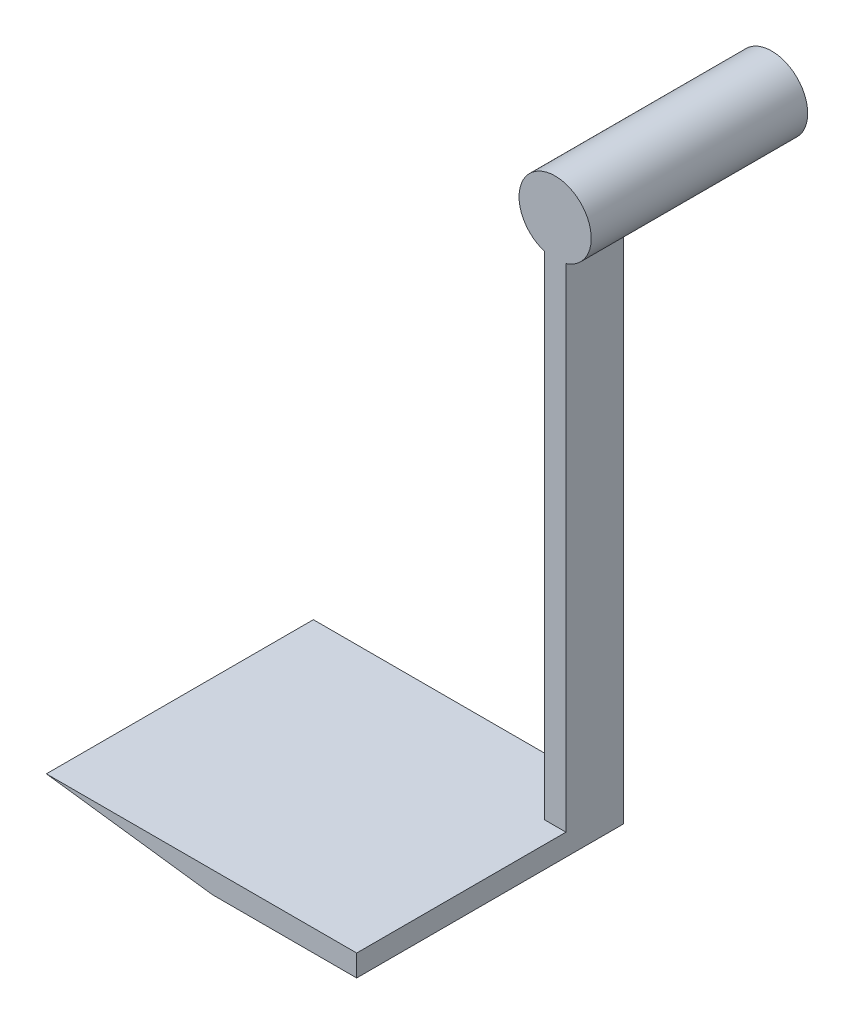
SolidWorks part; units mm, degrees
ref_plane "前视基准面" through (0, 0, 0) normal (0, 0, 1) x (1, 0, 0)
ref_plane "上视基准面" through (0, 0, 0) normal (0, 1, 0) x (1, 0, 0)
ref_plane "右视基准面" through (0, 0, 0) normal (1, 0, 0) x (0, 0, -1)
sketch "草图1" plane through (0, 0, 0) normal (0, 0, 1) x (1, 0, 0)
  line L0 (-19.7143, -1.7788) -> (-56.9643, -1.7788)
  line L1 (-56.9643, -1.7788) -> (-33.9643, -4.7788)
  line L2 (-33.9643, -4.7788) -> (-13.9643, -4.7788)
  line L3 (-13.9643, -4.7788) -> (-13.9643, 66.4515)
  line L5 (-16.9643, 66.4515) -> (-16.9643, -1.7788)
  line L6 (-16.9643, -1.7788) -> (-19.7143, -1.7788)
  arc A0 (-13.9643, 66.4515) -> (-16.9643, 66.4515) centre (-15.4643, 71.2212) ccw
  dimension "D6" = 10
  dimension "D1" = 40
  dimension "D2" = 3
  dimension "D3" = 3
  dimension "D4" = 20
  dimension "D5" = 76
  dimension "D7" = 1.5
extrude "凸台-拉伸1" add sketch "草图1" along normal blind 37 contours L5 L6 L0 L1 L2 L3 A0
sketch "草图8" plane through (-13.9643, 0, 0) normal (1, 0, 0) x (0, 0, -1)
  line L0 (-37, -4.7788) -> (0, -4.7788) construction
  line L1 (-37, 76.2212) -> (-8, 76.2212)
  line L2 (-37, 76.2212) -> (-37, -1.7788)
  line L3 (-37, -1.7788) -> (-8, -1.7788)
  line L4 (-8, 76.2212) -> (-8, -1.7788)
  line L5 (0, -4.7788) -> (0, 66.4515) construction
  dimension "D1" = 3
  dimension "D2" = 8
extrude "切除-拉伸3" cut sketch "草图8" against normal mid plane 20
sketch "草图10" plane through (0, 0, 0) normal (0, 0, -1) x (-1, 0, 0)
  circle A0 centre (15.4643, 71.2212) radius 5
extrude "凸台-拉伸4" add sketch "草图10" along normal blind 22
sketch "草图11" plane through (0, 0, -22) normal (0, 0, -1) x (-1, 0, 0)
  circle A0 centre (15.4643, 71.2212) radius 2.5
extrude "切除-拉伸4" cut sketch "草图11" against normal blind 20
